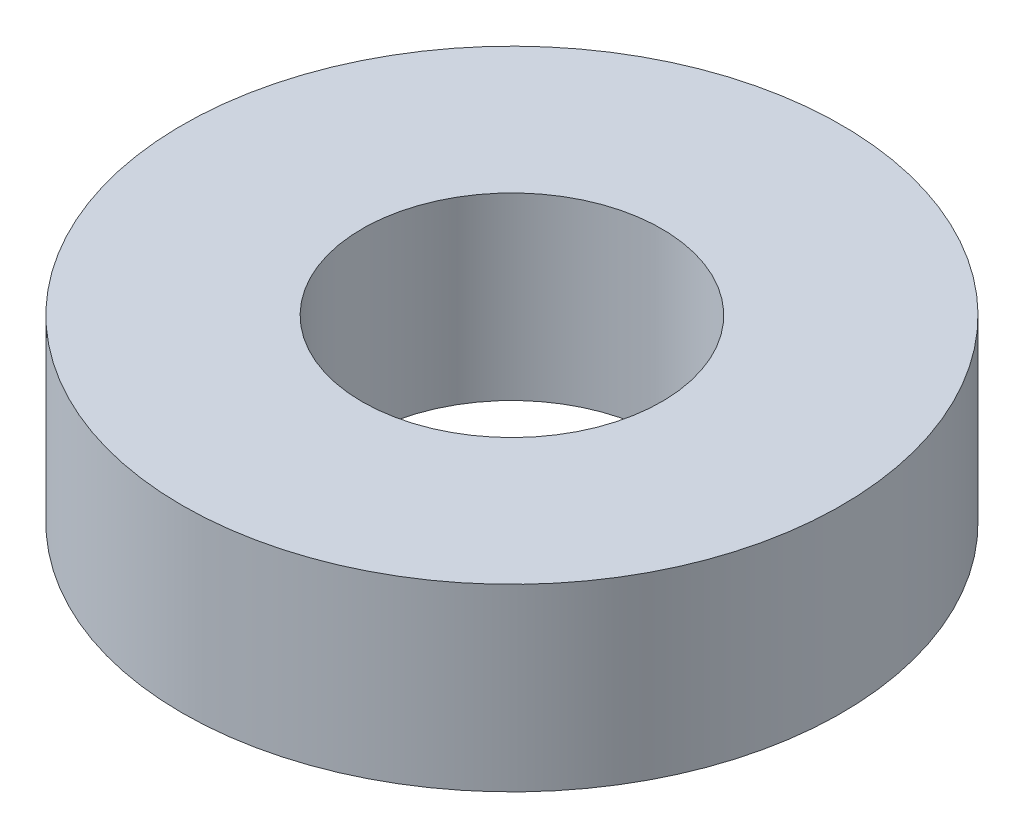
SolidWorks part; units mm, degrees
material "不锈钢 (铁素体)"
ref_plane "前视基准面" through (0, 0, 0) normal (0, 0, 1) x (1, 0, 0)
ref_plane "上视基准面" through (0, 0, 0) normal (0, 1, 0) x (1, 0, 0)
ref_plane "右视基准面" through (0, 0, 0) normal (1, 0, 0) x (0, 0, -1)
sketch "草图1" plane through (0, 0, 0) normal (0, 1, 0) x (1, 0, 0)
  circle A0 centre (0, 0) radius 2.5
  circle A1 centre (0, 0) radius 5.5
  dimension "D1" = 5
  dimension "D2" = 11
extrude "凸台-拉伸1" add sketch "草图1" along normal blind 3
